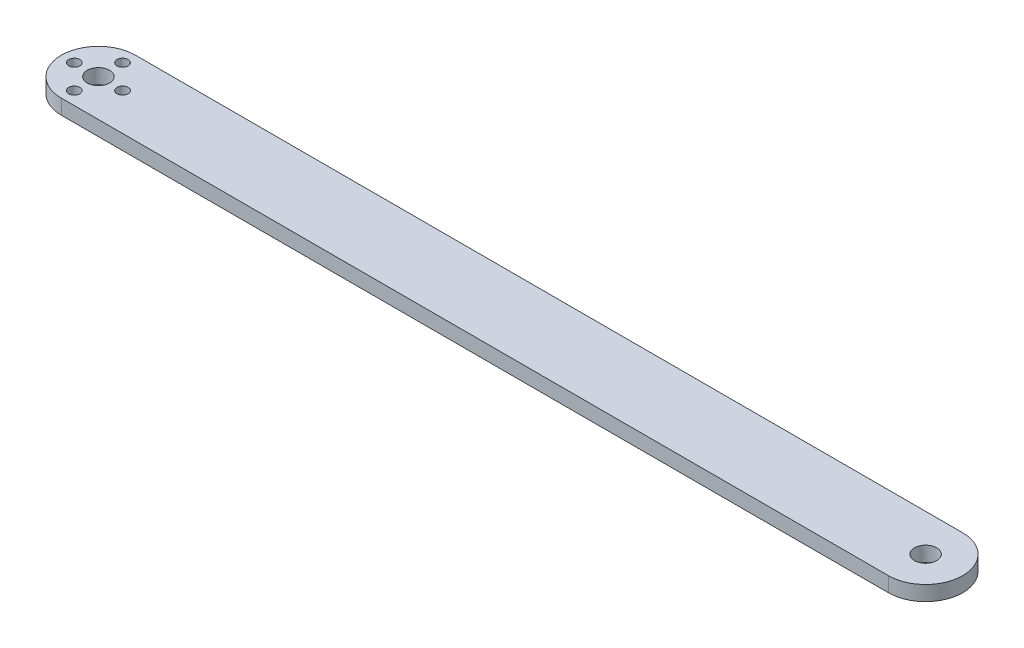
SolidWorks part; units mm, degrees
ref_plane "前视基准面" through (0, 0, 0) normal (0, 0, 1) x (1, 0, 0)
ref_plane "上视基准面" through (0, 0, 0) normal (0, 1, 0) x (1, 0, 0)
ref_plane "右视基准面" through (0, 0, 0) normal (1, 0, 0) x (0, 0, -1)
other "Configuration Table"
sketch "草图1" plane through (0, 0, 0) normal (0, 1, 0) x (1, 0, 0)
  line L0 (-111.375, 0) -> (111.375, 0) construction
  line L1 (-111.375, 10) -> (111.375, 10)
  line L2 (-111.375, -10) -> (111.375, -10)
  arc A0 (-111.375, 10) -> (-111.375, -10) centre (-111.375, 0) ccw
  arc A1 (111.375, -10) -> (111.375, 10) centre (111.375, 0) ccw
  circle A2 centre (-111.375, 0) radius 3
  circle A3 centre (111.375, 0) radius 3
  point P2 (0, 0)
  dimension "D2" = 10
  dimension "D3" = 6
  dimension "D4" = 6
  dimension "D1" = 222.75
extrude "凸台-拉伸1" add sketch "草图1" along normal blind 4
sketch "草图2" plane through (0, 4, 0) normal (0, 1, 0) x (1, 0, 0)
  circle A0 centre (-111.375, 6.5) radius 1.5
  circle A1 centre (-111.375, 0) radius 3 construction
  circle A2 centre (-111.375, 0) radius 3 construction
  dimension "D1" = 3
  dimension "D2" = 6.5
extrude "切除-拉伸1" cut sketch "草图2" against normal blind 4
pattern_circular "阵列(圆周)1" count 4 over 360 about axis through (-111.375, 0, 0) along (0, 1, 0) of "切除-拉伸1"
